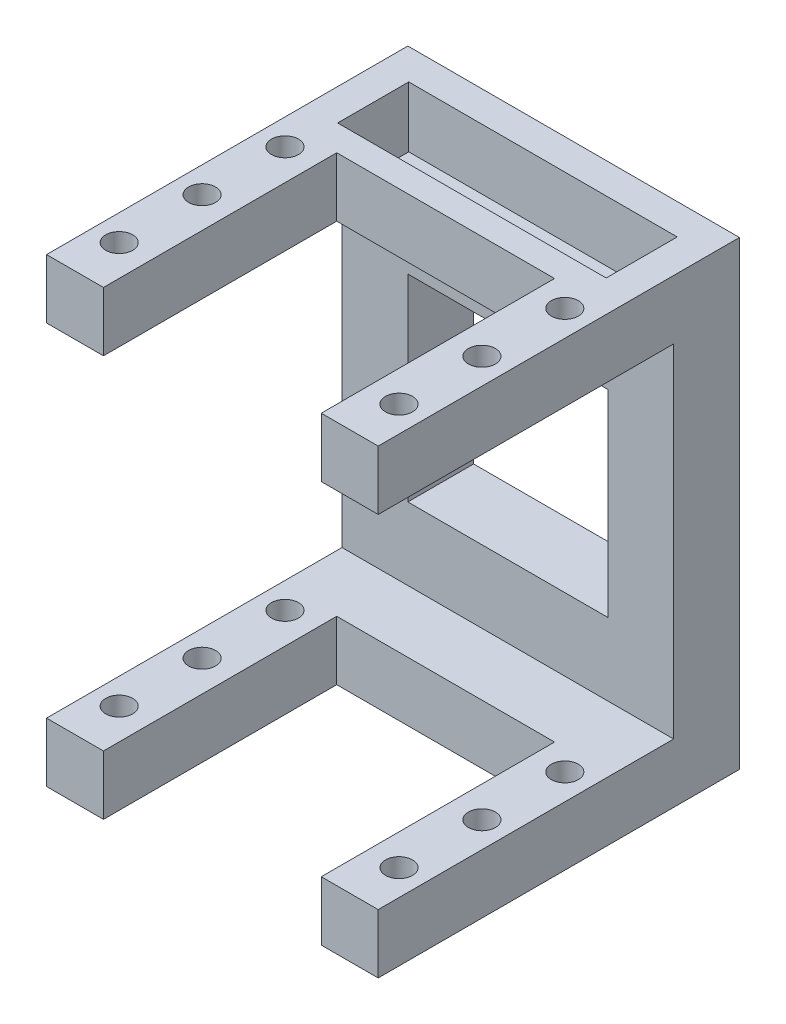
SolidWorks part; units mm, degrees
ref_plane "Front Plane" through (0, 0, 0) normal (0, 0, 1) x (1, 0, 0)
ref_plane "Top Plane" through (0, 0, 0) normal (0, 1, 0) x (1, 0, 0)
ref_plane "Right Plane" through (0, 0, 0) normal (1, 0, 0) x (0, 0, -1)
sketch "Sketch1" plane through (0, 0, 0) normal (0, 0, 1) x (1, 0, 0)
  line L1 (-16, -22.225) -> (16, -22.225)
  line L2 (-16, -22.225) -> (-16, 22.225)
  line L3 (-16, 22.225) -> (16, 22.225)
  line L4 (16, -22.225) -> (16, 22.225)
  line L5 (-16, -22.225) -> (16, 22.225) construction
  line L6 (-16, 22.225) -> (16, -22.225) construction
  point P0 (0, 0)
  dimension "D1" = 32
  dimension "D2" = 44.45
extrude "Boss-Extrude1" add sketch "Sketch1" against normal blind 50.8
sketch "Sketch2" plane through (16, 0, 0) normal (1, 0, 0) x (0, 0, -1)
  line L0 (0, 16) -> (35.3, 16) construction
  line L1 (0, -16) -> (35.3, -16) construction
  line L2 (0, 16.508) -> (35.808, 16.508)
  line L3 (35.3, 16) -> (35.3, -16) construction
  line L4 (35.808, 16.508) -> (35.808, -16.508)
  line L5 (0, -16.508) -> (35.808, -16.508)
  line L6 (0, 16.508) -> (0, -16.508)
  dimension "D1" = 0.508
extrude "Cut-Extrude1" cut sketch "Sketch2" against normal up to surface (32 mm away) up to face at (-16, 0, -25.4)
sketch "Sketch3" plane through (0, 22.225, 0) normal (0, 1, 0) x (1, 0, 0)
  line L0 (-10, 0) -> (-10, 29.3) construction
  line L2 (10, 0) -> (10, 29.3) construction
  line L4 (10, 29.3) -> (-10, 29.3) construction
  line L6 (-10.508, 7.3) -> (-10.508, 29.808)
  line L7 (10.508, 29.808) -> (-10.508, 29.808)
  line L8 (10.508, 7.3) -> (10.508, 29.808)
  line L9 (-16, 0) -> (16, 0)
  line L12 (-16, 7.3) -> (-10.508, 7.3)
  line L14 (16, 0) -> (16, 7.3)
  line L15 (-16, 0) -> (-16, 7.3)
  line L16 (-16, 50.8) -> (-16, 0) construction
  line L17 (10.508, 7.3) -> (16, 7.3)
  line L18 (-10.508, 0) -> (-10.508, 29.808) construction
  line L19 (16, 50.8) -> (16, 0) construction
  line L20 (10.508, 0) -> (10.508, 29.808) construction
  dimension "D1" = 0.508
extrude "Cut-Extrude2" cut sketch "Sketch3" against normal up to surface (44.45 mm away) up to face at (0, -22.225, -25.4)
sketch "Sketch4" plane through (-16, 0, 0) normal (-1, 0, 0) x (0, 0, 1)
  line L0 (-50.8, -22.225) -> (-7.3, -22.225) construction
  line L1 (-50.8, 22.225) -> (-42.158, 22.225)
  line L2 (-50.8, 22.225) -> (-50.8, -22.225)
  line L3 (-50.8, -22.225) -> (-42.158, -22.225)
  line L4 (-42.158, 22.225) -> (-42.158, -22.225)
  line L5 (-35.808, -16.508) -> (-35.808, 16.508) construction
  dimension "D1" = 6.35
extrude "Cut-Extrude3" cut sketch "Sketch4" against normal through all
sketch "Sketch6" plane through (0, 22.225, 0) normal (0, 1, 0) x (1, 0, 0)
  line L0 (-12.954, 39.2002) -> (12.954, 39.2002)
  line L1 (-12.7, 38.9462) -> (12.7, 38.9462) construction
  line L2 (-12.7, 38.9462) -> (-12.7, 32.5962) construction
  line L3 (-12.7, 32.5962) -> (12.7, 32.5962) construction
  line L4 (12.7, 38.9462) -> (12.7, 32.5962) construction
  line L5 (12.954, 39.2002) -> (12.954, 32.3422)
  line L6 (-12.954, 32.3422) -> (12.954, 32.3422)
  line L7 (-12.954, 39.2002) -> (-12.954, 32.3422)
  dimension "D1" = 0.254
extrude "Cut-Extrude4" cut sketch "Sketch6" against normal blind 5.842
sketch "Sketch7" plane through (0, 22.225, 0) normal (0, 1, 0) x (1, 0, 0)
  line L0 (0, 0) -> (0, 57.543) construction
  circle A0 centre (-13.5, 11.808) radius 1.3
  circle A1 centre (-13.5, 19.808) radius 1.3
  circle A2 centre (-13.5, 27.808) radius 1.3
  circle A3 centre (13.5, 27.808) radius 1.3
  circle A4 centre (13.5, 19.808) radius 1.3
  circle A5 centre (13.5, 11.808) radius 1.3
extrude "Cut-Extrude5" cut sketch "Sketch7" against normal up to surface (44.45 mm away)
sketch "Sketch8" plane through (0, 0, -42.158) normal (0, 0, -1) x (-1, 0, 0)
  line L0 (9.65, -9.525) -> (9.65, 9.525)
  line L2 (-9.65, 9.525) -> (-9.65, -9.525)
  line L4 (16, -22.225) -> (16, 22.225)
  line L5 (16, 22.225) -> (-16, 22.225)
  line L6 (-16, 22.225) -> (-16, -22.225)
  line L7 (-16, -22.225) -> (16, -22.225)
  line L8 (16, -22.225) -> (16, 22.225) construction
  line L9 (16, 22.225) -> (-16, 22.225) construction
  line L10 (-16, 22.225) -> (-16, -22.225) construction
  line L11 (-16, -22.225) -> (16, -22.225) construction
  line L12 (-9.65, -9.525) -> (9.65, -9.525)
  line L14 (9.65, 9.525) -> (-9.65, 9.525)
  line L16 (3.3, 9.525) -> (-3.3, 9.525) construction
  line L17 (-3.3, -9.525) -> (3.3, -9.525) construction
  line L18 (-9.65, 15.875) -> (-9.65, -15.875) construction
  line L19 (9.65, 15.875) -> (-9.65, 15.875) construction
  line L20 (9.65, -15.875) -> (9.65, 15.875) construction
  line L21 (-3.3, 9.525) -> (-3.3, -9.525) construction
  line L22 (3.3, -9.525) -> (3.3, 9.525) construction
  line L23 (-9.65, -15.875) -> (9.65, -15.875) construction
  dimension "D1" = 0
  dimension "D2" = 6.35
  dimension "D3" = 6.35
extrude "Cut-Extrude6" cut sketch "Sketch8" against normal through all
